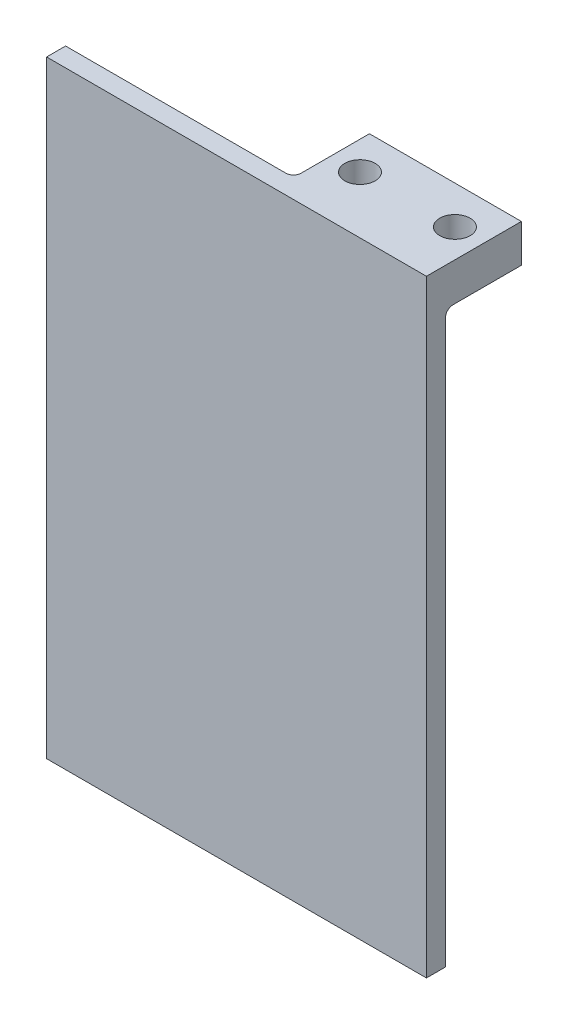
SolidWorks part; units mm, degrees
ref_plane "前视基准面" through (0, 0, 0) normal (0, 0, 1) x (1, 0, 0)
ref_plane "上视基准面" through (0, 0, 0) normal (0, 1, 0) x (1, 0, 0)
ref_plane "右视基准面" through (0, 0, 0) normal (1, 0, 0) x (0, 0, -1)
sketch "草图1" plane through (0, 0, 0) normal (0, 0, 1) x (1, 0, 0)
  line L1 (-50, 80) -> (50, 80)
  line L2 (-50, 80) -> (-50, -80)
  line L3 (-50, -80) -> (50, -80)
  line L4 (50, 80) -> (50, -80)
  line L5 (0, -80) -> (0, 80) construction
  line L6 (-50, 0) -> (50, 0) construction
  point P0 (0, 0)
  dimension "D1" = 160
  dimension "D2" = 100
extrude "凸台-拉伸1" add sketch "草图1" along normal blind 5
sketch "草图2" plane through (0, 80, 0) normal (0, 1, 0) x (1, 0, 0)
  line L1 (50, 0) -> (10, 0)
  line L2 (50, 0) -> (50, 20)
  line L3 (50, 20) -> (10, 20)
  line L4 (10, 0) -> (10, 20)
  dimension "D1" = 20
  dimension "D2" = 40
extrude "凸台-拉伸2" add sketch "草图2" against normal blind 10
sketch "草图3" plane through (0, 80, 0) normal (0, 1, 0) x (1, 0, 0)
  line L0 (50, -5) -> (50, 20) construction
  line L1 (10, 20) -> (10, 0) construction
  circle A0 centre (17.5, 10) radius 4
  circle A1 centre (42.5, 10) radius 4
  point P6 (0, 0)
  point P9 (10, 10)
  dimension "D1" = 8
  dimension "D2" = 7.5
  dimension "D3" = 25
extrude "切除-拉伸1" cut sketch "草图3" against normal blind 10
fillet "圆角1" radius 2 2 edges at (30, 70, 0) (10, 75, 0)
